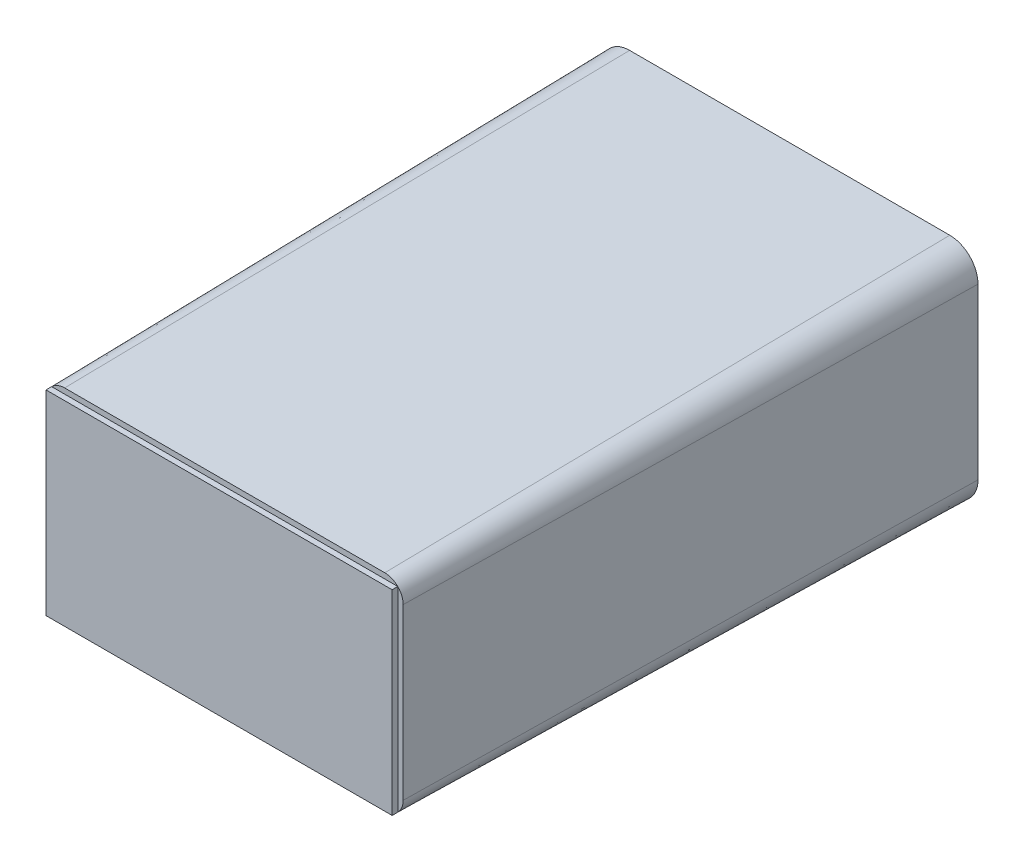
SolidWorks part; units mm, degrees
ref_plane "前视基准面" through (0, 0, 0) normal (0, 0, 1) x (1, 0, 0)
ref_plane "上视基准面" through (0, 0, 0) normal (0, 1, 0) x (1, 0, 0)
ref_plane "右视基准面" through (0, 0, 0) normal (1, 0, 0) x (0, 0, -1)
sketch "草图1" plane through (0, 0, 0) normal (0, 0, 1) x (1, 0, 0)
  line L1 (-85, 60) -> (85, 60)
  line L2 (-100, 45) -> (-100, -45)
  line L3 (-85, -60) -> (85, -60)
  line L4 (100, 45) -> (100, -45)
  arc A0 (-85, 60) -> (-100, 45) centre (-85, 45) ccw
  arc A1 (-100, -45) -> (-85, -60) centre (-85, -45) ccw
  arc A2 (85, -60) -> (100, -45) centre (85, -45) ccw
  arc A3 (85, 60) -> (100, 45) centre (85, 45) cw
  point P7 (-100, 60)
  point P12 (100, -60)
  point P15 (100, 60)
  dimension "D5" = 15
  dimension "D1" = 200
  dimension "D2" = 120
  dimension "D3" = 60
  dimension "D4" = 100
extrude "凸台-拉伸1" add sketch "草图1" along normal blind 300 draft 1
shell "抽壳1" thickness 4
ref_plane "基准面4" through (0, 0, 4) normal (0, 0, 1) x (1, 0, 0)
sketch "草图3" plane through (0, 0, 4) normal (0, 0, 1) x (1, 0, 0)
sketch "草图4" plane through (0, 0, 4) normal (0, 0, 1) x (1, 0, 0)
  line L0 (0, 0) -> (0, 50.7629)
  line L1 (85, 50.7629) -> (-85, 50.7629) construction
  line L2 (0, 50.7629) -> (2.9342, 50.7629)
  line L3 (2.9342, 50.7629) -> (2.9342, 0)
  line L4 (2.9342, 0) -> (2.9342, -0.3954)
  line L5 (2.9342, -0.3954) -> (0, -0.3954)
  line L6 (0, -0.3954) -> (0, 0.4666)
extrude "凸台-拉伸2" add sketch "草图4" along normal blind 60 contours L6 L5 L4 L3 L2 L0
ref_plane "基准面5" through (0, 0, 64) normal (0, 0, 1) x (1, 0, 0)
sketch "草图5" plane through (6.0137, 0, 64) normal (0, 0, 1) x (1, 0, 0)
  line L2 (0, 50.7629) -> (90.7629, 50.7629)
  line L3 (0, 50.7629) -> (0, 0)
  line L4 (0, 0) -> (90.7629, 0)
  line L5 (90.7629, 50.7629) -> (90.7629, 0)
extrude "凸台-拉伸3" add sketch "草图5" along normal blind 3
sketch "草图6" plane through (0, 0, 64) normal (0, 0, 1) x (1, 0, 0)
  line L0 (0, 25.1838) -> (6.0137, 28.7664)
  line L1 (0, -0.3954) -> (0, 50.7629) construction
  line L2 (6.0137, 50.7629) -> (6.0137, 0) construction
  line L3 (6.0137, 28.7664) -> (6.0137, 21.6011)
  line L4 (6.0137, 21.6011) -> (0, 25.1838)
  dimension "D1" = 7
  dimension "D2" = 7
extrude "凸台-拉伸4" add sketch "草图6" along normal blind 3
ref_plane "基准面6" through (0, 0, 67) normal (0, 0, 1) x (1, 0, 0)
sketch "草图7" plane through (0, 0, 67) normal (0, 0, 1) x (1, 0, 0)
  line L0 (2.9342, 50.7629) -> (2.9342, -0.3954) construction
  line L1 (0, 50.7629) -> (2.9342, 50.7629)
  line L2 (0, 50.7629) -> (0, -0.3954)
  line L3 (0, -0.3954) -> (2.9342, -0.3954)
  line L4 (2.9342, 50.7629) -> (2.9342, -0.3954)
  line L5 (2.9342, -0.3954) -> (0, -0.3954) construction
mirror "镜向1" about plane through (0, -0.3954, 64) normal (0, -1, 0) of "凸台-拉伸3", "凸台-拉伸2"
ref_plane "基准面7" through (0, 0, 300) normal (0, 0, 1) x (1, 0, 0)
sketch "草图8" plane through (0, 0, 300) normal (0, 0, 1) x (1, 0, 0)
  line L1 (-91.9038, -51.9038) -> (91.9038, -51.9038)
  line L2 (-91.9038, -51.9038) -> (-91.9038, 51.9038)
  line L3 (-91.9038, 51.9038) -> (91.9038, 51.9038)
  line L4 (91.9038, -51.9038) -> (91.9038, 51.9038)
  arc A0 (-94.7635, -45) -> (-85, -54.7635) centre (-85, -45) ccw construction
  arc A1 (94.7635, 45) -> (85, 54.7635) centre (85, 45) ccw construction
extrude "凸台-拉伸11" add sketch "草图8" along normal blind 3
